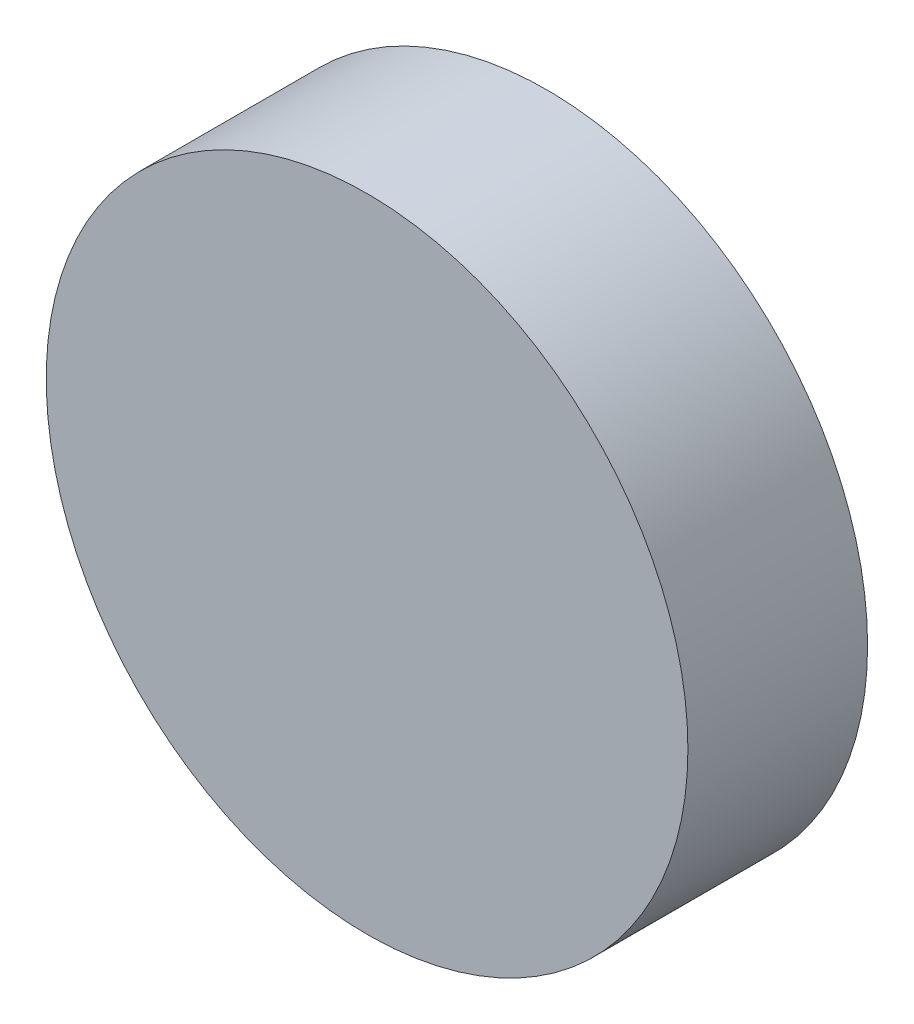
SolidWorks part; units mm, degrees
ref_plane "Front Plane" through (0, 0, 0) normal (0, 0, 1) x (1, 0, 0)
ref_plane "Top Plane" through (0, 0, 0) normal (0, 1, 0) x (1, 0, 0)
ref_plane "Right Plane" through (0, 0, 0) normal (1, 0, 0) x (0, 0, -1)
sketch "Sketch1" plane through (0, 0, 0) normal (0, 0, 1) x (1, 0, 0)
  circle A0 centre (0, 0) radius 125
  dimension "D1" = 250
extrude "Boss-Extrude1" add sketch "Sketch1" along normal blind 70 contours A0
